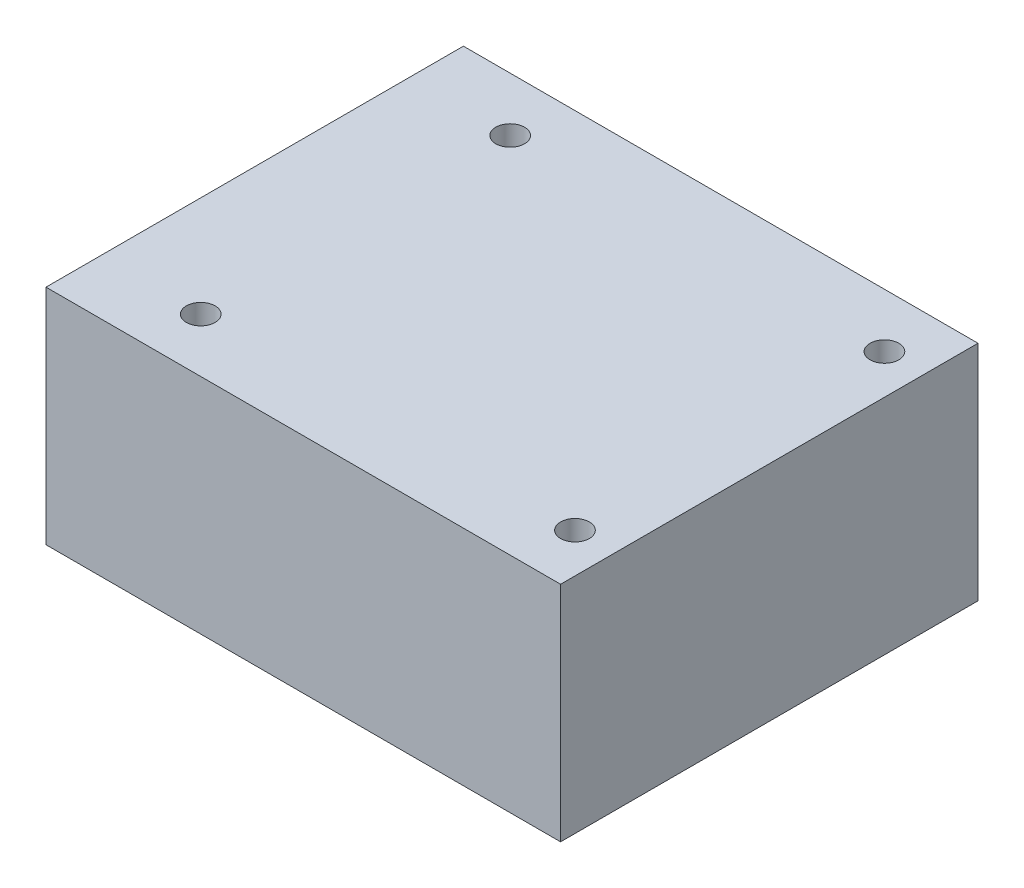
SolidWorks part; units mm, degrees
ref_plane "前基準面" through (0, 0, 0) normal (0, 0, 1) x (1, 0, 0)
ref_plane "上基準面" through (0, 0, 0) normal (0, 1, 0) x (1, 0, 0)
ref_plane "右基準面" through (0, 0, 0) normal (1, 0, 0) x (0, 0, -1)
sketch "草圖1" plane through (0, 0, 0) normal (0, 1, 0) x (1, 0, 0)
  line L0 (-21.75, 0) -> (-35.75, 0) construction
  line L1 (-35.75, 29) -> (35.75, 29)
  line L2 (-35.75, 29) -> (-35.75, -29)
  line L3 (-35.75, -29) -> (35.75, -29)
  line L4 (35.75, 29) -> (35.75, -29)
  line L5 (-35.75, 29) -> (35.75, -29) construction
  line L6 (-35.75, -29) -> (35.75, 29) construction
  line L7 (30.25, 21.5) -> (-21.75, 21.5) construction
  line L8 (30.25, 21.5) -> (30.25, -21.5) construction
  line L9 (30.25, -21.5) -> (-21.75, -21.5) construction
  line L10 (-21.75, 21.5) -> (-21.75, -21.5) construction
  circle A0 centre (-21.75, 21.5) radius 2
  circle A1 centre (30.25, 21.5) radius 2
  circle A2 centre (30.25, -21.5) radius 2
  circle A3 centre (-21.75, -21.5) radius 2
  point P0 (0, 0)
  dimension "D5" = 4
  dimension "D1" = 71.5
  dimension "D2" = 58
  dimension "D3" = 52
  dimension "D4" = 43
  dimension "D6" = 5.5
extrude "伸長1" add sketch "草圖1" along normal blind 31
